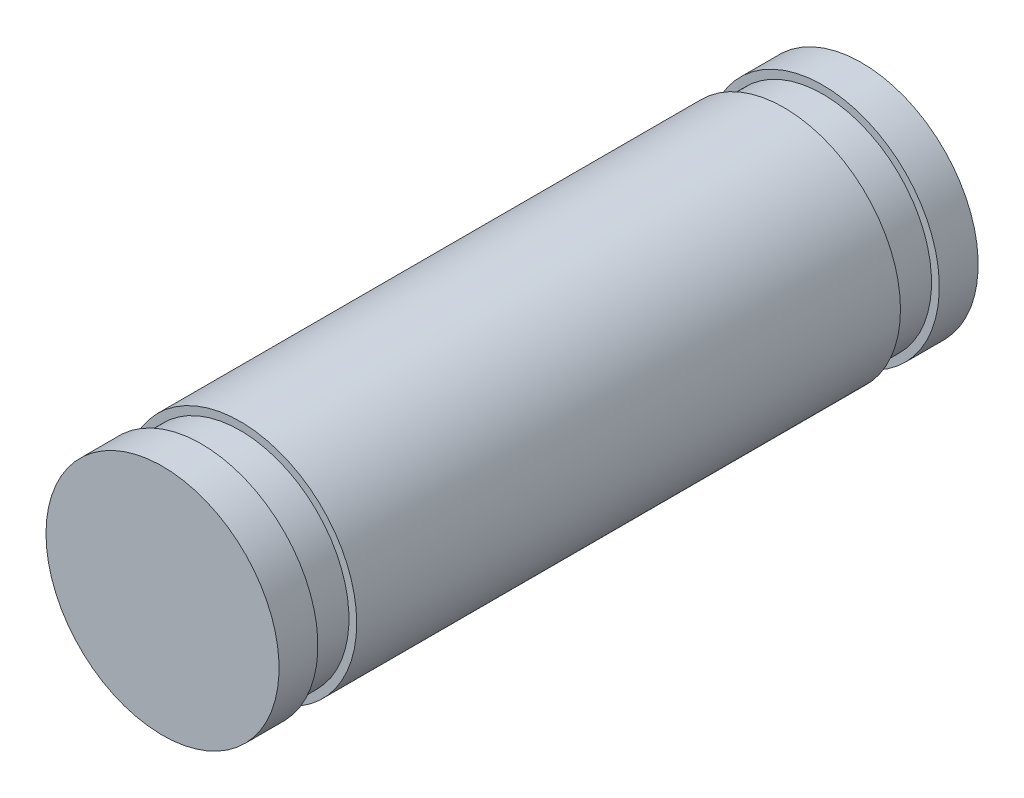
SolidWorks part; units mm, degrees
ref_plane "Front Plane" through (0, 0, 0) normal (0, 0, 1) x (1, 0, 0)
ref_plane "Top Plane" through (0, 0, 0) normal (0, 1, 0) x (1, 0, 0)
ref_plane "Right Plane" through (0, 0, 0) normal (1, 0, 0) x (0, 0, -1)
sketch "Sketch1" plane through (0, 0, 0) normal (0, 0, 1) x (1, 0, 0)
  circle A0 centre (0, 0) radius 1.5
  dimension "D1" = 3
extrude "Boss-Extrude1" add sketch "Sketch1" along normal blind 7
sketch "Sketch2" plane through (0, 0, 0) normal (0, 0, -1) x (-1, 0, 0)
  circle A0 centre (0, 0) radius 1.4
  dimension "D1" = 2.8
extrude "Boss-Extrude2" add sketch "Sketch2" along normal blind 0.5
sketch "Sketch3" plane through (0, 0, -0.5) normal (0, 0, -1) x (-1, 0, 0)
  circle A0 centre (0, 0) radius 1.5
  dimension "D1" = 3
extrude "Boss-Extrude3" add sketch "Sketch3" along normal blind 0.5
ref_plane "Plane2" through (0, 0, 3.5) normal (0, 0, 1) x (1, 0, 0)
mirror "Mirror1" about plane through (0, 0, 3.5) normal (0, 0, 1) of "Boss-Extrude2", "Boss-Extrude3"
